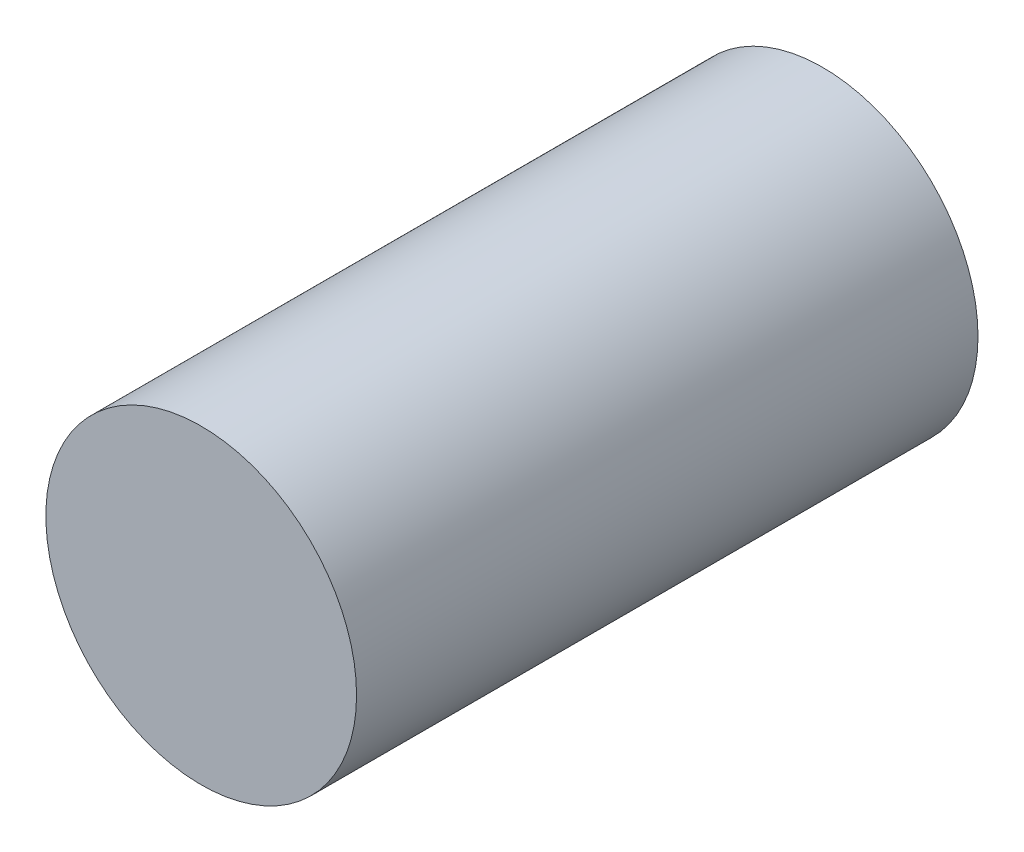
SolidWorks part; units mm, degrees
ref_plane "Front Plane" through (0, 0, 0) normal (0, 0, 1) x (1, 0, 0)
ref_plane "Top Plane" through (0, 0, 0) normal (0, 1, 0) x (1, 0, 0)
ref_plane "Right Plane" through (0, 0, 0) normal (1, 0, 0) x (0, 0, -1)
sketch "Sketch1" plane through (0, 0, 0) normal (0, 0, 1) x (1, 0, 0)
  circle A0 centre (0, 0) radius 6.35
  dimension "D1" = 12.7
extrude "Boss-Extrude1" add sketch "Sketch1" along normal blind 25.4
